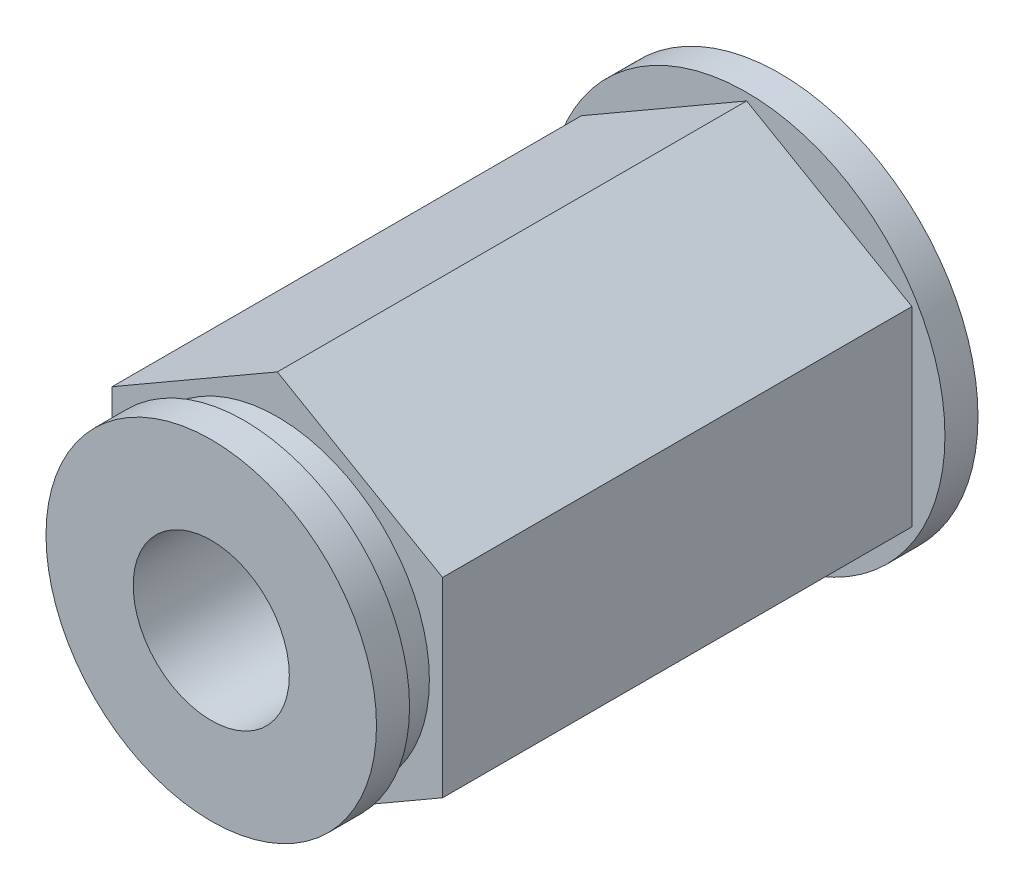
SolidWorks part; units mm, degrees
material "7075-O (SS)"
ref_plane "Plan de face" through (0, 0, 0) normal (0, 0, 1) x (1, 0, 0)
ref_plane "Plan de dessus" through (0, 0, 0) normal (0, 1, 0) x (1, 0, 0)
ref_plane "Plan de droite" through (0, 0, 0) normal (1, 0, 0) x (0, 0, -1)
sketch "Esquisse1" plane through (0, 0, 0) normal (0, 0, 1) x (1, 0, 0)
  line L1 (0, 7.3323) -> (-6.35, 3.6662)
  line L2 (-6.35, 3.6662) -> (-6.35, -3.6662)
  line L3 (-6.35, -3.6662) -> (0, -7.3323)
  line L4 (0, -7.3323) -> (6.35, -3.6662)
  line L5 (6.35, -3.6662) -> (6.35, 3.6662)
  line L6 (6.35, 3.6662) -> (0, 7.3323)
  circle A0 centre (0, 0) radius 6.35 construction
  dimension "D1" = 12.7
extrude "Boss.-Extru.1" add sketch "Esquisse1" along normal blind 19.304
sketch "Esquisse2" plane through (0, 0, 0) normal (0, 0, 1) x (1, 0, 0)
  circle A0 centre (0, 0) radius 7.62
  dimension "D1" = 15.24
extrude "Boss.-Extru.2" add sketch "Esquisse2" along normal blind 1.27
sketch "Esquisse3" plane through (0, 0, 19.304) normal (0, 0, 1) x (1, 0, 0)
  circle A0 centre (0, 0) radius 5.842
  dimension "D1" = 11.684
extrude "Boss.-Extru.3" add sketch "Esquisse3" along normal blind 1.27
sketch "Esquisse4" plane through (0, 0, 20.574) normal (0, 0, 1) x (1, 0, 0)
  circle A0 centre (0, 0) radius 6.35
  dimension "D1" = 12.7
extrude "Boss.-Extru.4" add sketch "Esquisse4" along normal blind 1.27
sketch "Esquisse5" plane through (0, 0, 0) normal (0, 0, 1) x (1, 0, 0)
  circle A0 centre (0, 0) radius 3
  dimension "D1" = 6
extrude "Enlèv. mat.-Extru.1" cut sketch "Esquisse5" along normal through all
